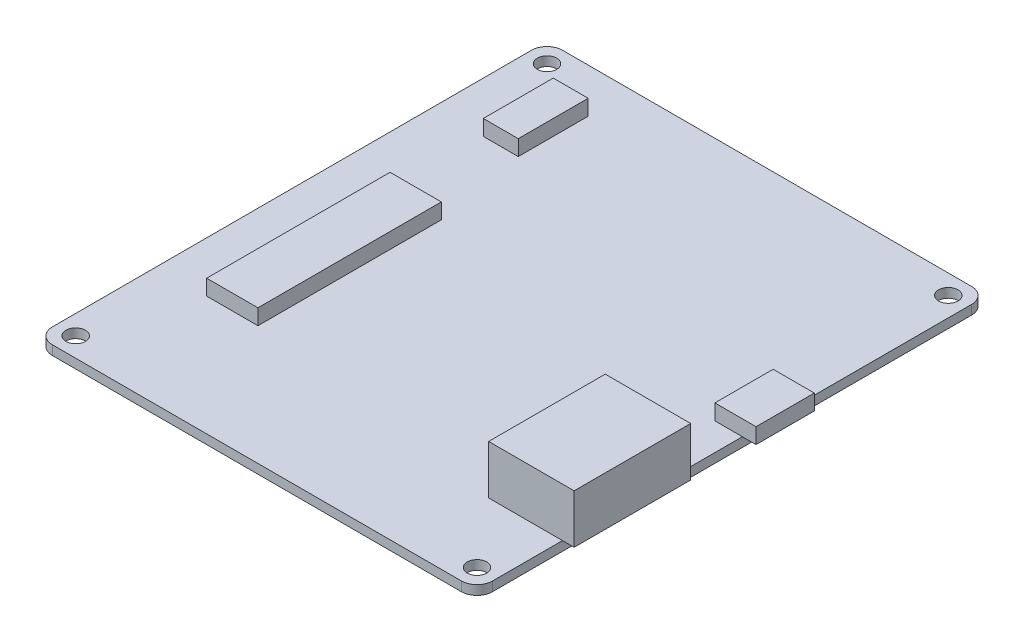
SolidWorks part; units mm, degrees
ref_plane "Front" through (0, 0, 0) normal (0, 0, 1) x (1, 0, 0)
ref_plane "Top" through (0, 0, 0) normal (0, 1, 0) x (1, 0, 0)
ref_plane "Right" through (0, 0, 0) normal (1, 0, 0) x (0, 0, -1)
sketch "草图1" plane through (0, 0, 0) normal (0, 1, 0) x (1, 0, 0)
  line L0 (-28.32, 32.825) -> (28.32, -32.825) construction
  line L1 (-26.32, -32.825) -> (26.32, -32.825)
  line L2 (-28.32, -30.825) -> (-28.32, 30.825)
  line L3 (-26.32, 32.825) -> (26.32, 32.825)
  line L4 (28.32, -30.825) -> (28.32, 30.825)
  line L5 (-28.32, -32.825) -> (28.32, 32.825) construction
  arc A0 (26.32, 32.825) -> (28.32, 30.825) centre (26.32, 30.825) cw
  arc A1 (26.32, -32.825) -> (28.32, -30.825) centre (26.32, -30.825) ccw
  arc A2 (-26.32, -32.825) -> (-28.32, -30.825) centre (-26.32, -30.825) cw
  arc A3 (-28.32, 30.825) -> (-26.32, 32.825) centre (-26.32, 30.825) cw
  dimension "D3" = 2
  dimension "D1" = 65.65
  dimension "D2" = 56.64
extrude "凸台-拉伸1" add sketch "草图1" along normal blind 1.2
hole_wizard "大小mm 暗销孔1" positions "草图2" profile "草图3" hole size "Ø2.5" standard "GB" end condition through all
sketch "草图2" plane through (0, 1.2, 0) normal (0, 1, 0) x (1, 0, 0)
  line L0 (26.32, 32.825) -> (-26.32, 32.825) construction
  line L1 (-28.32, 30.825) -> (-28.32, -30.825) construction
  line L2 (28.32, -30.825) -> (28.32, 30.825) construction
  line L3 (-26.32, -32.825) -> (26.32, -32.825) construction
  point P0 (-25.82, 30.325)
  point P2 (-25.82, -30.325)
  point P4 (25.82, -30.325)
  point P6 (25.82, 30.325)
  dimension "D1" = 2.5
  dimension "D2" = 2.5
  dimension "D3" = 2.5
  dimension "D4" = 2.5
sketch "草图3" plane through (-25.82, 1.2, -30.325) normal (1, 0, 0) x (0, 0, 1)
  line L0 (0, 0) -> (0, 1.2)
  line L1 (0, 1.2) -> (1.25, 1.2)
  line L2 (1.25, 1.2) -> (1.25, 0)
  line L5 (1.25, 0) -> (0, 0)
  line L11 (0, -6.35) -> (0, 107.95) construction
  dimension "通孔孔直径" = 2.5
  dimension "通孔孔深度" = 1.2
sketch "草图4" plane through (0, 1.2, 0) normal (0, 1, 0) x (1, 0, 0)
  line L0 (26.32, 32.825) -> (-26.32, 32.825) construction
  line L1 (-21.82, 6.125) -> (-15.22, 6.125)
  line L2 (-21.82, 6.125) -> (-21.82, -17.475)
  line L3 (-21.82, -17.475) -> (-15.22, -17.475)
  line L4 (-15.22, 6.125) -> (-15.22, -17.475)
  line L5 (-21.82, 27.125) -> (-17.32, 27.125)
  line L6 (-21.82, 27.125) -> (-21.82, 18.125)
  line L7 (-21.82, 18.125) -> (-17.32, 18.125)
  line L8 (-17.32, 27.125) -> (-17.32, 18.125)
  line L9 (24.78, 8.825) -> (30.08, 8.825)
  line L10 (24.78, 8.825) -> (24.78, 1.325)
  line L11 (24.78, 1.325) -> (30.08, 1.325)
  line L12 (30.08, 8.825) -> (30.08, 1.325)
  line L13 (-28.32, 30.825) -> (-28.32, -30.825) construction
  line L14 (28.32, -30.825) -> (28.32, 30.825) construction
  dimension "D1" = 23.6
  dimension "D2" = 6.6
  dimension "D3" = 4.5
  dimension "D4" = 5.3
  dimension "D5" = 7.5
  dimension "D6" = 9
  dimension "D7" = 5.7
  dimension "D8" = 6.5
  dimension "D9" = 12
  dimension "D10" = 1.76
  dimension "D11" = 24
extrude "凸台-拉伸2" add sketch "草图4" along normal blind 2
sketch "草图5" plane through (0, 1.2, 0) normal (0, 1, 0) x (1, 0, 0)
  line L0 (-26.32, -32.825) -> (26.32, -32.825) construction
  line L1 (18.82, -6.825) -> (29.82, -6.825)
  line L2 (18.82, -6.825) -> (18.82, -21.825)
  line L3 (18.82, -21.825) -> (29.82, -21.825)
  line L4 (29.82, -6.825) -> (29.82, -21.825)
  line L5 (28.32, -30.825) -> (28.32, 1.325) construction
  dimension "D1" = 15
  dimension "D2" = 11
  dimension "D3" = 11
  dimension "D4" = 1.5
extrude "凸台-拉伸3" add sketch "草图5" along normal blind 6.3
